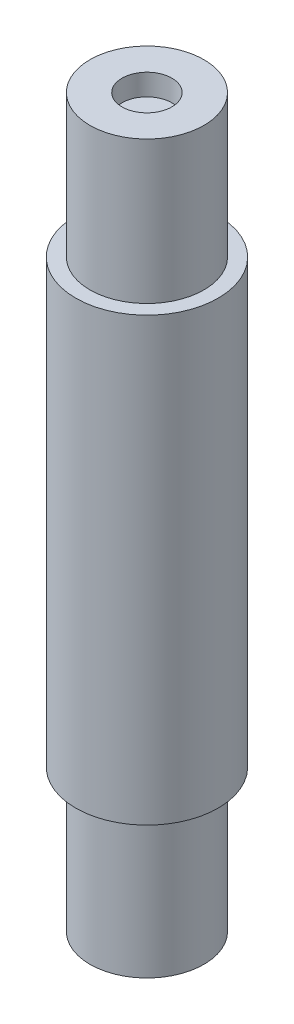
SolidWorks part; units mm, degrees
material "1060 Alloy"
ref_plane "Front Plane" through (0, 0, 0) normal (0, 0, 1) x (1, 0, 0)
ref_plane "Top Plane" through (0, 0, 0) normal (0, 1, 0) x (1, 0, 0)
ref_plane "Right Plane" through (0, 0, 0) normal (1, 0, 0) x (0, 0, -1)
sketch "Sketch1" plane through (0, 0, 0) normal (0, 1, 0) x (1, 0, 0)
  circle A0 centre (0, 0) radius 5
  dimension "D1" = 10
extrude "Boss-Extrude1" add sketch "Sketch1" along normal blind 31
sketch "Sketch2" plane through (0, 31, 0) normal (0, 1, 0) x (1, 0, 0)
  circle A0 centre (0, 0) radius 4
  dimension "D1" = 8
extrude "Boss-Extrude2" add sketch "Sketch2" along normal blind 10 and the other way offset from surface (41 mm away) 10 other way up to face at (0, 0, 5)
sketch "Sketch3" plane through (0, -10, 0) normal (0, -1, 0) x (1, 0, 0)
  circle A0 centre (0, 0) radius 1.75
  dimension "D1" = 3.5
extrude "Cut-Extrude1" cut sketch "Sketch3" against normal blind 1.5
sketch "Sketch4" plane through (0, 41, 0) normal (0, 1, 0) x (1, 0, 0)
  circle A0 centre (0, 0) radius 1.75
  dimension "D1" = 3.5
extrude "Cut-Extrude2" cut sketch "Sketch4" against normal blind 1.5
